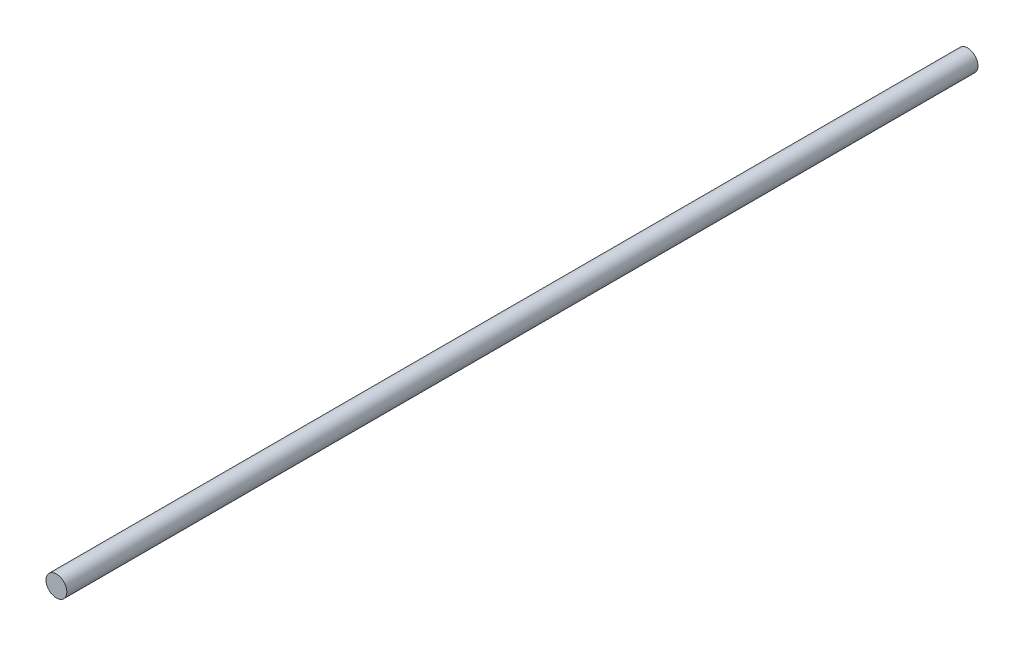
SolidWorks part; units mm, degrees
ref_plane "Front Plane" through (0, 0, 0) normal (0, 0, 1) x (1, 0, 0)
ref_plane "Top Plane" through (0, 0, 0) normal (0, 1, 0) x (1, 0, 0)
ref_plane "Right Plane" through (0, 0, 0) normal (1, 0, 0) x (0, 0, -1)
sketch "Sketch1" plane through (0, 0, 0) normal (0, 0, 1) x (1, 0, 0)
  circle A0 centre (0, 0) radius 4
  dimension "D1" = 8
extrude "Boss-Extrude1" add sketch "Sketch1" along normal blind 350 contours A0
cosmetic thread "Cosmetic Thread1" parameters "D2"=6.891
equation "\"acTubeOD\"= 300mm"
equation "\"acTubeThickness\"= 3mm"
equation "\"acTubeLength\"= 300mm"
equation "\"threadedRodDiam\"= 8mm"
equation "\"flange width\"= 24mm"
equation "\"D1@Boss-Extrude1\"=\"acTubeLength\"+50"
